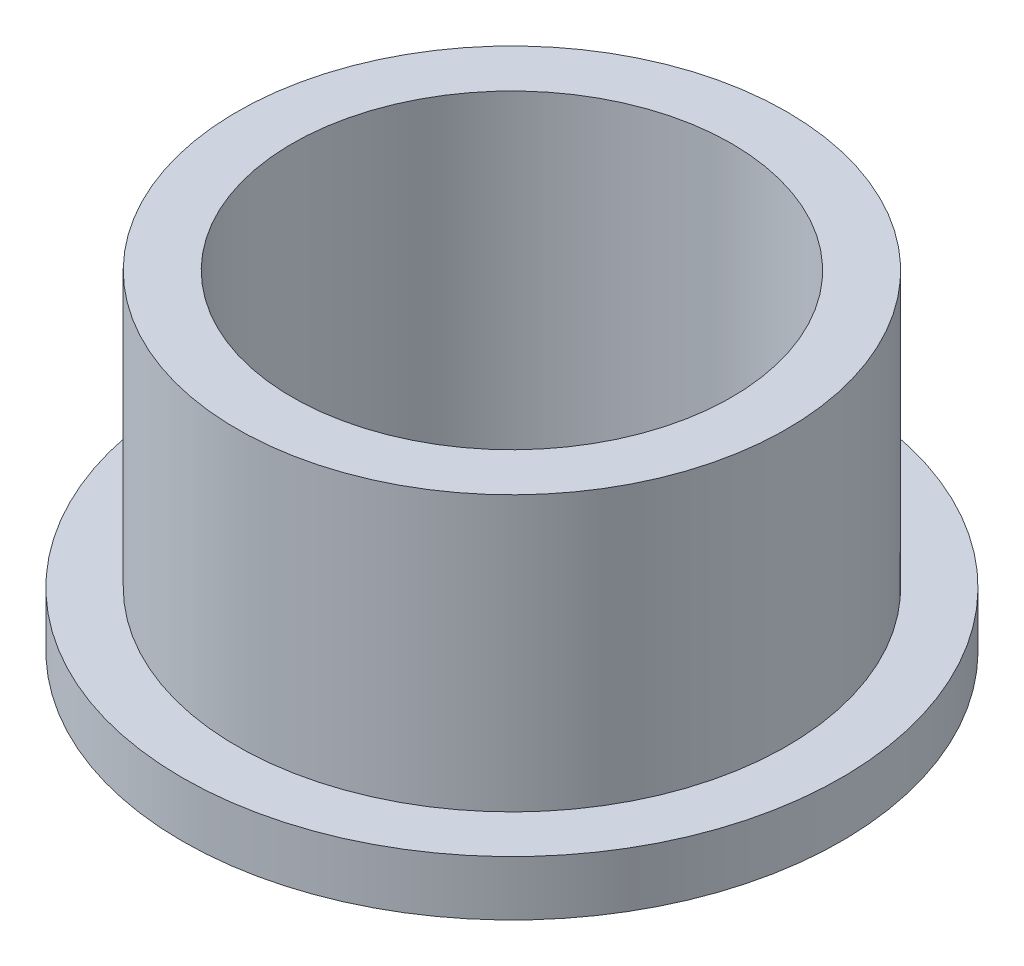
SolidWorks part; units mm, degrees
ref_plane "Front" through (0, 0, 0) normal (0, 0, 1) x (1, 0, 0)
ref_plane "Top" through (0, 0, 0) normal (0, 1, 0) x (1, 0, 0)
ref_plane "Right" through (0, 0, 0) normal (1, 0, 0) x (0, 0, -1)
sketch "Sketch1" plane through (0, 0, 0) normal (0, 1, 0) x (1, 0, 0)
  circle A0 centre (0, 0) radius 12.7
  circle A1 centre (0, 0) radius 15.8877
  circle A2 centre (0, 0) radius 19.05
  dimension "ID" = 25.4
  dimension "OD" = 31.7754
  dimension "FlangeOD" = 38.1
sketch "Sketch2" plane through (0, 0, 0) normal (0, 1, 0) x (1, 0, 0)
  circle A0 centre (0, 0) radius 12.7 construction
  circle A1 centre (0, 0) radius 15.8877 construction
  circle A2 centre (0, 0) radius 12.7
  circle A3 centre (0, 0) radius 15.8877
extrude "Boss-Extrude1" add sketch "Sketch2" along normal blind 19.05
sketch "Sketch3" plane through (0, 0, 0) normal (0, 1, 0) x (1, 0, 0)
  circle A0 centre (0, 0) radius 19.05 construction
  circle A1 centre (0, 0) radius 15.8877 construction
  circle A2 centre (0, 0) radius 19.05
  circle A3 centre (0, 0) radius 15.8877
extrude "Boss-Extrude2" add sketch "Sketch3" along normal blind 3.175
